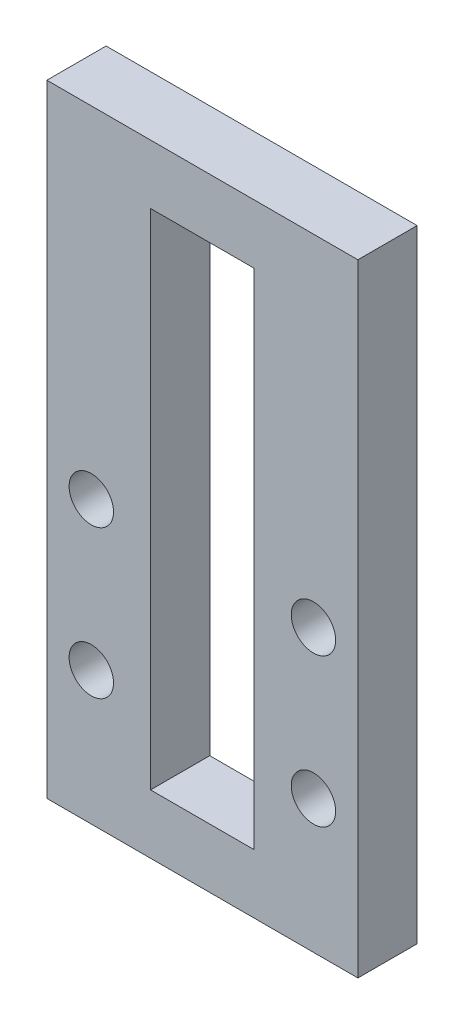
SolidWorks part; units mm, degrees
material "Thornel Mat VMA"
ref_plane "前视基准面" through (0, 0, 0) normal (0, 0, 1) x (1, 0, 0)
ref_plane "上视基准面" through (0, 0, 0) normal (0, 1, 0) x (1, 0, 0)
ref_plane "右视基准面" through (0, 0, 0) normal (1, 0, 0) x (0, 0, -1)
sketch "草图1" plane through (0, 0, 0) normal (0, 0, 1) x (1, 0, 0)
  line L0 (0, 36.2949) -> (0, -36.0138) construction
  line L1 (-40.9048, 0) -> (52.0636, 0) construction
  line L2 (10.5, -14) -> (10.5, 14) construction
  line L3 (-10.5, 14) -> (10.5, 14)
  line L4 (-10.5, 14) -> (-10.5, -14)
  line L5 (-10.5, -14) -> (10.5, -14)
  line L6 (34.5, 4) -> (34.5, -4)
  line L7 (10.5, 14) -> (10.5, 4)
  line L8 (10.5, 4) -> (34.5, 4)
  line L9 (10.5, -14) -> (10.5, -4)
  line L10 (10.5, -4) -> (34.5, -4)
  circle A0 centre (-7.5, 5) radius 1.5
  circle A1 centre (7.5, 5) radius 1.5
  circle A2 centre (-7.5, -5) radius 1.5
  circle A3 centre (7.5, -5) radius 1.5
  circle A4 centre (16.5, 0) radius 1.5
  circle A5 centre (31.5, 0) radius 1.5
  dimension "D1" = 3
  dimension "D2" = 10
  dimension "D3" = 15
  dimension "D4" = 3
  dimension "D5" = 9
  dimension "D8" = 3
  dimension "D9" = 15
  dimension "D10" = 3
  dimension "D11" = 6
  dimension "D6" = 24
  dimension "D7" = 3
  dimension "D12" = 4
  dimension "D13" = 4
extrude "凸台-拉伸1" add sketch "草图1" along normal blind 4
fillet "圆角1" radius 2 2 edges at (10.5, -4, 2) (10.5, 4, 2)
sketch "草图3" plane through (0, 0, 4) normal (0, 0, 1) x (1, 0, 0)
  line L1 (10.5, 14) -> (35.6387, 14)
  line L2 (10.5, 14) -> (10.5, -15.7039)
  line L3 (10.5, -15.7039) -> (35.6387, -15.7039)
  line L4 (35.6387, 14) -> (35.6387, -15.7039)
extrude "切除-拉伸1" cut sketch "草图3" against normal through all
sketch "草图4" plane through (0, 0, 4) normal (0, 0, 1) x (1, 0, 0)
  line L0 (10.5, -14) -> (10.5, 14) construction
  line L1 (-10.5, 14) -> (10.5, 14)
  line L2 (-10.5, 14) -> (-10.5, 28)
  line L3 (-10.5, 28) -> (10.5, 28)
  line L4 (10.5, 14) -> (10.5, 28)
  dimension "D1" = 14
extrude "凸台-拉伸2" add sketch "草图4" against normal up to surface (4 mm away) up to face at (0, 0, 0)
sketch "草图5" plane through (0, 0, 4) normal (0, 0, 1) x (1, 0, 0)
  line L0 (0, -14) -> (0, 28) construction
  line L1 (-10.5, -14) -> (10.5, -14) construction
  line L2 (10.5, 28) -> (-10.5, 28) construction
  line L4 (-3.5, 24) -> (3.5, 24)
  line L5 (-3.5, 24) -> (-3.5, -10)
  line L6 (-3.5, -10) -> (3.5, -10)
  line L7 (3.5, 24) -> (3.5, -10)
  circle A0 centre (7.5, 5) radius 1.5 construction
  dimension "D1" = 4
  dimension "D2" = 4
  dimension "D3" = 4
extrude "切除-拉伸2" cut sketch "草图5" against normal through all
